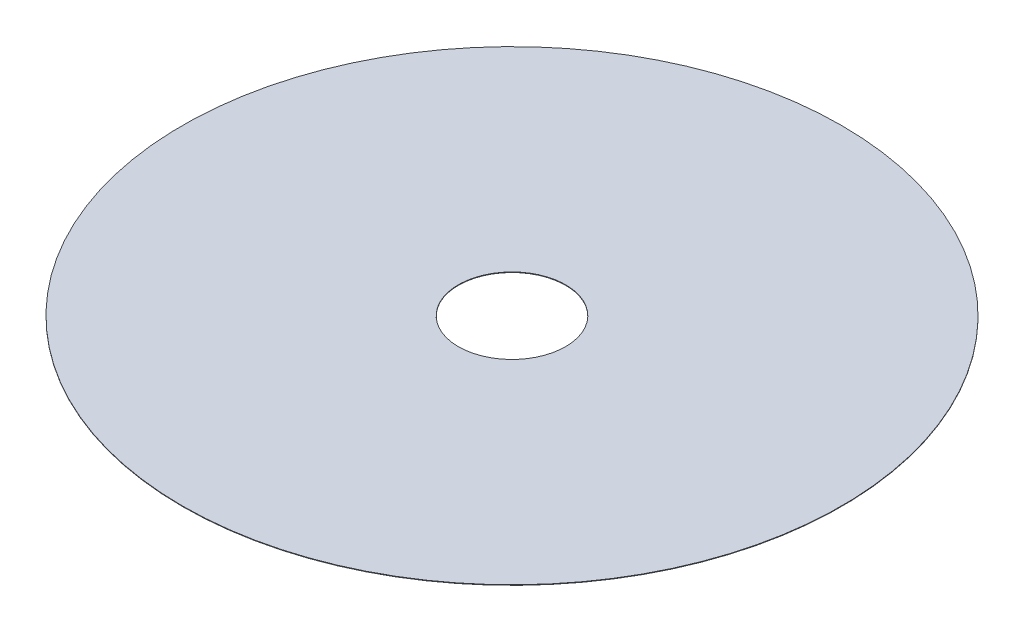
SolidWorks part; units mm, degrees
ref_plane "Front Plane" through (0, 0, 0) normal (0, 0, 1) x (1, 0, 0)
ref_plane "Top Plane" through (0, 0, 0) normal (0, 1, 0) x (1, 0, 0)
ref_plane "Right Plane" through (0, 0, 0) normal (1, 0, 0) x (0, 0, -1)
sketch "Sketch1" plane through (0, 0, 0) normal (0, 1, 0) x (1, 0, 0)
  circle A0 centre (0, 0) radius 24.534
  circle A1 centre (0, 0) radius 3.9925
  dimension "D1" = 49.068
  dimension "D2" = 7.985
extrude "Boss-Extrude1" add sketch "Sketch1" along normal blind 0.0388
equation "\"Upper_Mount_largest_radius\" =26.6"
equation "\"Lower_Mount_piston_rod_radius\"\t=3.4925"
equation "\"D1@Sketch1\"=((\"Upper_Mount_largest_radius\"*2)-1mm)*0.94"
equation "\"D2@Sketch1\"=(\"Lower_Mount_piston_rod_radius\"*2)+1mm"
equation "\"D1@Boss-Extrude1\"=\"Lower_Mount_piston_rod_radius\"/90"
equation "\"Upper_mount_wall_thickness\" =4"
equation "\"Lower_Mount_piston_rod_length\" =149"
equation "\"Piston_orifice_dia\"=0.30711"
equation "\"Spring_inner_dia\" =80"
equation "\"Spring_wire_dia\" =8"
